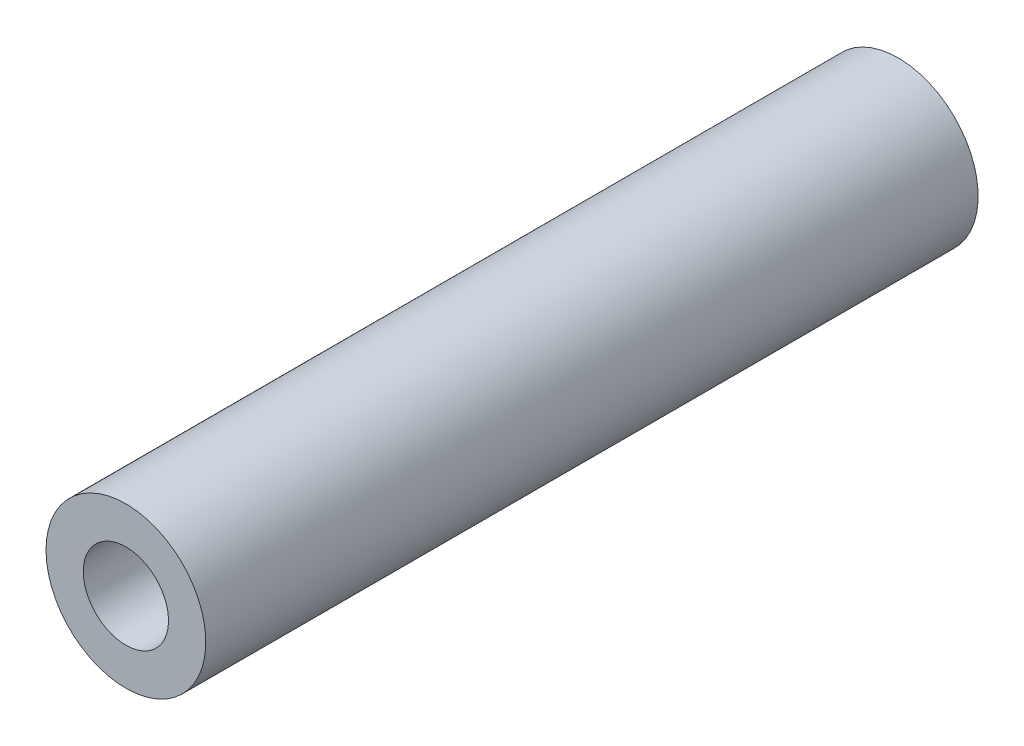
SolidWorks part; units mm, degrees
material "6061-T6 (SS)"
ref_plane "Front Plane" through (0, 0, 0) normal (0, 0, 1) x (1, 0, 0)
ref_plane "Top Plane" through (0, 0, 0) normal (0, 1, 0) x (1, 0, 0)
ref_plane "Right Plane" through (0, 0, 0) normal (1, 0, 0) x (0, 0, -1)
sketch "Sketch1" plane through (0, 0, 0) normal (0, 0, 1) x (1, 0, 0)
  circle A0 centre (0, 0) radius 6
  circle A1 centre (0, 0) radius 3.2
extrude "Spacer" add sketch "Sketch1" along normal blind 58
